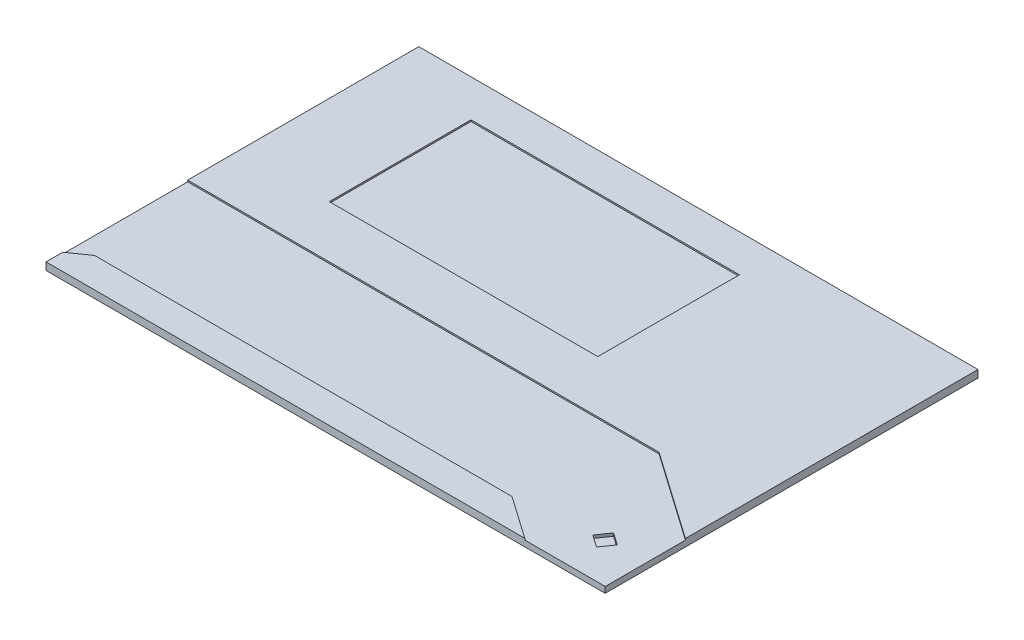
SolidWorks part; units mm, degrees
ref_plane "Alzado" through (0, 0, 0) normal (0, 0, 1) x (1, 0, 0)
ref_plane "Planta" through (0, 0, 0) normal (0, 1, 0) x (1, 0, 0)
ref_plane "Vista lateral" through (0, 0, 0) normal (1, 0, 0) x (0, 0, -1)
sketch "Croquis3" plane through (0, 0, 0) normal (0, 1, 0) x (1, 0, 0)
  line L0 (-375, 250) -> (375, -250) construction
  line L1 (-375, 250) -> (375, 250)
  line L2 (-375, 250) -> (-375, -250)
  line L3 (-375, -250) -> (375, -250)
  line L4 (375, 250) -> (375, -250)
  line L5 (210, -77.5485) -> (375, -123.1137)
  line L6 (-255, 212.4515) -> (105, 212.4515)
  line L7 (-255, 212.4515) -> (-255, 22.4515)
  line L8 (-255, 22.4515) -> (105, 22.4515)
  line L9 (105, 212.4515) -> (105, 22.4515)
  line L10 (-240, -77.5485) -> (210, -77.5485)
  line L11 (-240, -77.5485) -> (-240, -197.5485)
  line L12 (-240, -197.5485) -> (210, -197.5485)
  line L13 (210, -77.5485) -> (210, -197.5485)
  line L14 (210, -197.5485) -> (375, -243.1137)
  line L15 (375, -243.1137) -> (375, -123.1137)
  point P4 (0, 0)
  dimension "D1" = 750
  dimension "D2" = 500
  dimension "D3" = 360
  dimension "D4" = 190
  dimension "10" = 120
  dimension "D6" = 100
  dimension "D8" = 450
  dimension "D9" = 120
  dimension "D10" = 105
  dimension "D11" = 190
extrude "Saliente-Extruir1" add sketch "Croquis3" against normal blind 10 contours L2 L1 L4 L3
sketch "Croquis5" plane through (0, 0, 0) normal (0, 1, 0) x (1, 0, 0)
  line L0 (-375, 250) -> (-375, -250) construction
  line L1 (-255, 200) -> (105, 200)
  line L2 (-255, 200) -> (-255, 10)
  line L3 (-255, 10) -> (105, 10)
  line L4 (105, 200) -> (105, 10)
  line L5 (-375, 250) -> (375, 250) construction
  line L6 (-350, -60) -> (210, -60)
  line L8 (-350, -210) -> (210, -210)
  line L10 (210, -210) -> (267.1259, -250)
  line L11 (-375, -250) -> (375, -250) construction
  line L12 (257.2948, -60) -> (375, -142.4181)
  line L13 (375, 250) -> (375, -250) construction
  line L14 (-350, -210) -> (-375, -227.5052)
  line L15 (-350, -60) -> (-375, -60)
  line L16 (-375, -60) -> (-375, -227.5052)
  line L18 (210, -60) -> (257.2948, -60)
  line L19 (267.1259, -250) -> (375, -250)
  line L20 (375, -250) -> (375, -142.4181)
  dimension "D1" = 120
  dimension "D3" = 360
  dimension "D4" = 190
  dimension "D5" = 50
  dimension "D6" = 70
  dimension "D7" = 150
  dimension "D9" = 215
  dimension "D10" = 215
  dimension "D11" = 150
extrude "Cortar-Extruir2" cut sketch "Croquis5" against normal blind 2
sketch "Croquis7" plane through (0, -2, 0) normal (0, 1, 0) x (1, 0, 0)
  line L0 (210, -210) -> (267.1259, -250) construction
  line L1 (318.4125, -182.1454) -> (334.7956, -193.617)
  line L2 (318.4125, -182.1454) -> (306.941, -198.5285)
  line L3 (306.941, -198.5285) -> (323.324, -210)
  line L4 (334.7956, -193.617) -> (323.324, -210)
  line L5 (375, -142.4181) -> (257.2948, -60) construction
  line L8 (267.1259, -250) -> (375, -250) construction
  dimension "D1" = 20
  dimension "D2" = 65
  dimension "D3" = 20
  dimension "D4" = 65
  dimension "D5" = 40
extrude "Cortar-Extruir3" cut sketch "Croquis7" against normal blind 4
sketch "Croquis8" plane through (0, -10, 0) normal (0, -1, 0) x (1, 0, 0)
  line L0 (-260.1757, -6.3096) -> (113.6375, -203.391) construction
  line L2 (-68.6778, -107.2709) -> (-118.6778, -107.2709)
  line L3 (-68.6778, -107.2709) -> (-68.6778, -80.91)
  line L4 (-68.6778, -80.91) -> (-118.6778, -80.91)
  line L5 (-118.6778, -107.2709) -> (-118.6778, -80.91)
  dimension "D1" = 50
  dimension "D2" = 26.3609
extrude "Saliente-Extruir2" add sketch "Croquis8" along normal blind 15
sketch "Croquis9" plane through (0, -10, 0) normal (0, -1, 0) x (1, 0, 0)
  line L0 (-68.6778, -107.2709) -> (-68.6778, -80.91) construction
  line L1 (-68.6778, -120.0905) -> (-228.6778, -120.0905)
  line L2 (-68.6778, -120.0905) -> (-68.6778, -68.0905)
  line L3 (-68.6778, -68.0905) -> (-228.6778, -68.0905)
  line L4 (-228.6778, -120.0905) -> (-228.6778, -68.0905)
  line L5 (-228.6778, -68.0905) -> (-68.6778, -120.0905) construction
  line L6 (-118.6778, -80.91) -> (-68.6778, -107.2709) construction
  point P4 (-68.6778, -94.0905)
  point P7 (-148.6778, -94.0905)
  point P12 (-93.6778, -94.0905)
  dimension "D1" = 52
  dimension "D2" = 160
extrude "Saliente-Extruir3" add sketch "Croquis9" along normal blind 10
